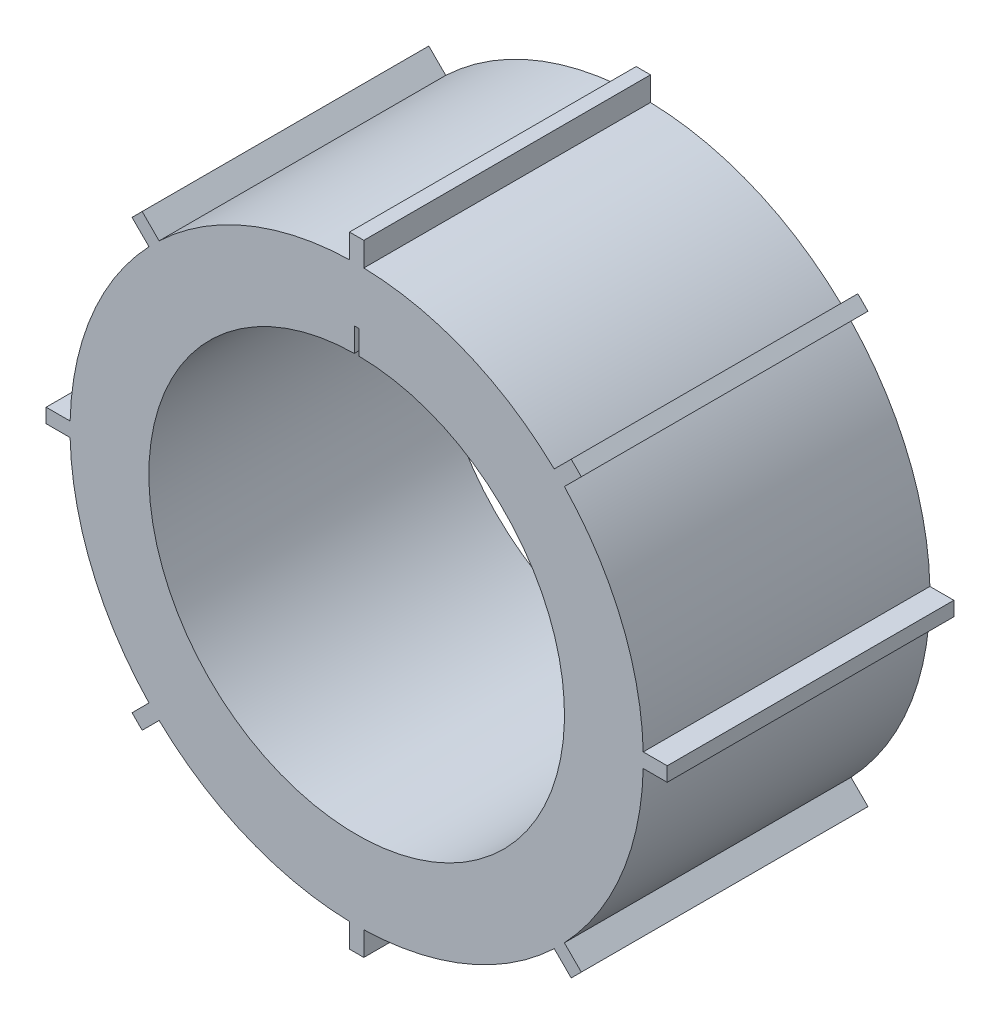
SolidWorks part; units mm, degrees
ref_plane "Front Plane" through (0, 0, 0) normal (0, 0, 1) x (1, 0, 0)
ref_plane "Top Plane" through (0, 0, 0) normal (0, 1, 0) x (1, 0, 0)
ref_plane "Right Plane" through (0, 0, 0) normal (1, 0, 0) x (0, 0, -1)
ref_plane "Plane1"
sketch "Sketch1" plane through (0, 0, 0) normal (0, 0, 1) x (1, 0, 0)
  circle A0 centre (0, 0) radius 60
  circle A1 centre (0, 0) radius 43.5
  dimension "D1" = 87
  dimension "D2" = 120
extrude "Extrusion1" add sketch "Sketch1" along normal blind 60 contours A0 A1
ref_plane "Plane2"
ref_plane "Plane3"
sketch "Sketch3" plane through (0, 0, 60) normal (0, 0, 1) x (1, 0, 0)
  line L0 (-0.5, 48.5) -> (-0.5, 43.4971)
  line L1 (0.5, 43.4971) -> (0.5, 48.5)
  line L2 (0.5, 48.5) -> (-0.5, 48.5)
  arc A0 (0.5, 43.4971) -> (-0.5, 43.4971) centre (0, 0) ccw
extrude "Extrusion3" cut sketch "Sketch3" against normal blind 60
sketch "Sketch4" plane through (0, 0, 60) normal (0, 0, 1) x (1, 0, 0)
  line L0 (41.3525, 43.4738) -> (44.9013, 47.0226)
  line L1 (1.5, 59.9812) -> (1.5, 65)
  line L2 (-1.5, 59.9812) -> (-1.5, 65)
  line L3 (1.5, 65) -> (-1.5, 65)
  line L4 (47.0226, 44.9013) -> (44.9013, 47.0226)
  line L5 (43.4738, 41.3525) -> (47.0226, 44.9013)
  line L6 (59.9812, 1.5) -> (65, 1.5)
  line L7 (65, -1.5) -> (65, 1.5)
  line L8 (59.9812, -1.5) -> (65, -1.5)
  line L9 (43.4738, -41.3525) -> (47.0226, -44.9013)
  line L10 (44.9013, -47.0226) -> (47.0226, -44.9013)
  line L11 (41.3525, -43.4738) -> (44.9013, -47.0226)
  line L12 (1.5, -59.9812) -> (1.5, -65)
  line L13 (-1.5, -65) -> (1.5, -65)
  line L14 (-1.5, -59.9812) -> (-1.5, -65)
  line L15 (-41.3525, -43.4738) -> (-44.9013, -47.0226)
  line L16 (-47.0226, -44.9013) -> (-44.9013, -47.0226)
  line L17 (-43.4738, -41.3525) -> (-47.0226, -44.9013)
  line L18 (-59.9812, -1.5) -> (-65, -1.5)
  line L19 (-65, 1.5) -> (-65, -1.5)
  line L20 (-59.9812, 1.5) -> (-65, 1.5)
  line L21 (-43.4738, 41.3525) -> (-47.0226, 44.9013)
  line L22 (-44.9013, 47.0226) -> (-47.0226, 44.9013)
  line L23 (-41.3525, 43.4738) -> (-44.9013, 47.0226)
  arc A1 (1.5, 59.9812) -> (-1.5, 59.9812) centre (0, 0) ccw
  arc A2 (43.4738, 41.3525) -> (41.3525, 43.4738) centre (0, 0) ccw
  arc A3 (59.9812, -1.5) -> (59.9812, 1.5) centre (0, 0) ccw
  arc A4 (41.3525, -43.4738) -> (43.4738, -41.3525) centre (0, 0) ccw
  arc A5 (-1.5, -59.9812) -> (1.5, -59.9812) centre (0, 0) ccw
  arc A6 (-43.4738, -41.3525) -> (-41.3525, -43.4738) centre (0, 0) ccw
  arc A7 (-59.9812, 1.5) -> (-59.9812, -1.5) centre (0, 0) ccw
  arc A8 (-41.3525, 43.4738) -> (-43.4738, 41.3525) centre (0, 0) ccw
  point P39 (0, 0)
  dimension "D1" = 8
extrude "Boss-Extrude1" add sketch "Sketch4" against normal through all
